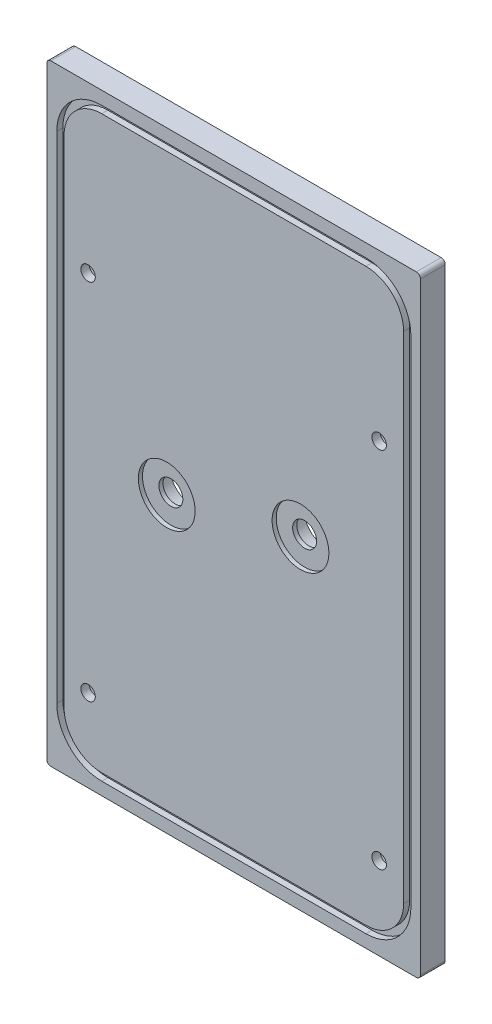
SolidWorks part; units mm, degrees
material "Melamine resin"
ref_plane "Plano frontal" through (0, 0, 0) normal (0, 0, 1) x (1, 0, 0)
ref_plane "Plano superior" through (0, 0, 0) normal (0, 1, 0) x (1, 0, 0)
ref_plane "Plano direito" through (0, 0, 0) normal (1, 0, 0) x (0, 0, -1)
sketch "Esboço1" plane through (0, 0, 0) normal (0, 0, 1) x (1, 0, 0)
  line L1 (-90.5, -148) -> (90.5, -148)
  line L2 (-90.5, -148) -> (-90.5, 148)
  line L3 (-90.5, 148) -> (90.5, 148)
  line L4 (90.5, -148) -> (90.5, 148)
  line L5 (-90.5, -148) -> (90.5, 148) construction
  line L6 (-90.5, 148) -> (90.5, -148) construction
  point P0 (0, 0)
  dimension "D1" = 181
  dimension "D2" = 296
extrude "Ressalto-extrusão1" add sketch "Esboço1" along normal blind 12
fillet "Filete1" radius 2 1 edges at (-90.5, 148, 6)
fillet "Filete2" radius 2 3 edges at (-90.5, -148, 6) (90.5, -148, 6) (90.5, 148, 6)
sketch "Esboço2" plane through (0, 0, 12) normal (0, 0, 1) x (1, 0, 0)
  line L5 (-63.9, -140.1) -> (64.1, -140.1)
  line L6 (-83.9, -120.1) -> (-83.9, 119.9)
  line L7 (-63.9, 139.9) -> (64.1, 139.9)
  line L8 (84.1, -120.1) -> (84.1, 119.9)
  line L9 (-83.9, -140.1) -> (84.1, 139.9) construction
  line L10 (-83.9, 139.9) -> (84.1, -140.1) construction
  arc A0 (84.1, -120.1) -> (64.1, -140.1) centre (64.1, -120.1) cw
  arc A1 (-63.9, -140.1) -> (-83.9, -120.1) centre (-63.9, -120.1) cw
  arc A2 (-63.9, 139.9) -> (-83.9, 119.9) centre (-63.9, 119.9) ccw
  arc A3 (84.1, 119.9) -> (64.1, 139.9) centre (64.1, 119.9) ccw
  point P6 (0.1, -0.1)
  dimension "D3" = 20
  dimension "D1" = 168
  dimension "D2" = 280
sketch "Esboço4" plane through (0, 0, 0) normal (0, 1, 0) x (1, 0, 0)
  line L0 (-83.9, -12) -> (-63.9, -12) construction
  line L2 (-85.665, -12.565) -> (-82.135, -12.565)
  line L3 (-85.665, -12.565) -> (-85.665, -9.035)
  line L4 (-85.665, -9.035) -> (-82.135, -9.035)
  line L5 (-82.135, -12.565) -> (-82.135, -9.035)
  line L6 (-85.665, -12.565) -> (-82.135, -9.035) construction
  line L7 (-85.665, -9.035) -> (-82.135, -12.565) construction
  circle A0 centre (-83.9, -10.8) radius 1.765 construction
  dimension "D1" = 3.53
  dimension "D2" = 1.2
sweep "Varredura de corte1" cut profiles "Esboço4" path "Esboço2"
sketch "Esboço6" plane through (0, 0, 0) normal (0, 0, 1) x (1, 0, 0)
  line L0 (88.5, 148) -> (-88.5, 148) construction
  line L1 (-70.5, -108) -> (70.5, -108) construction
  line L2 (-70.5, -108) -> (-70.5, 68) construction
  line L3 (-70.5, 68) -> (70.5, 68) construction
  line L4 (70.5, -108) -> (70.5, 68) construction
  line L5 (-70.5, -108) -> (70.5, 68) construction
  line L6 (-70.5, 68) -> (70.5, -108) construction
  line L8 (-90.5, 146) -> (-90.5, -146) construction
  line L9 (-88.5, -148) -> (88.5, -148) construction
  point P0 (0, 0)
  dimension "D1" = 80
  dimension "D2" = 20
  dimension "D3" = 40
hole_wizard "Rebaixo para parafuso com cabeça panela de M61" positions "Esboço8" profile "Esboço7" counterbore size "M6" standard "ISO" end condition through all
sketch "Esboço8" plane through (0, 0, 0) normal (0, 0, -1) x (-1, 0, 0)
  point P0 (-70.5, 68)
  point P1 (70.5, 68)
  point P4 (70.5, -108)
  point P7 (-70.5, -108)
sketch "Esboço7" plane through (70.5, 68, 0) normal (1, 0, 0) x (0, 1, 0)
  line L0 (0, 0) -> (0, 12)
  line L1 (0, 12) -> (3.5, 12)
  line L3 (3.5, 12) -> (3.5, 8)
  line L4 (3.5, 8) -> (6.5, 8)
  line L5 (6.5, 8) -> (6.5, 0)
  line L7 (6.5, 0) -> (0, 0)
  line L11 (0, -6.35) -> (0, 107.95) construction
  dimension "Thru Hole Dia." = 7
  dimension "Thru Hole Depth" = 12
  dimension "C'Bore Dia." = 13
  dimension "C'Bore Depth" = 8
sketch "Esboço9" plane through (0, 0, 0) normal (0, 0, -1) x (-1, 0, 0)
  line L0 (-90.5, -146) -> (-90.5, 146) construction
  line L1 (90.5, 146) -> (90.5, -146) construction
  line L2 (-88.5, 148) -> (88.5, 148) construction
  circle A0 centre (32.4, -6) radius 5.8
  circle A1 centre (-32.4, 8.8) radius 5.8
  dimension "D1" = 11.6
  dimension "D2" = 11.6
  dimension "D3" = 58.1
  dimension "D4" = 58.1
  dimension "D5" = 139.2
  dimension "D6" = 154
extrude "Corte-extrusão1" cut sketch "Esboço9" against normal up to next
sketch "Esboço10" plane through (0, 0, 0) normal (0, 0, -1) x (-1, 0, 0)
  line L0 (-32.4, 8.8) -> (-32.4, 31.045) construction
  line L1 (32.4, -6) -> (32.4, 18.3317) construction
  circle A0 centre (32.4, -6) radius 10.275
  circle A1 centre (-32.4, 8.8) radius 10.275
  dimension "D1" = 20.55
  dimension "D2" = 20.55
extrude "Corte-extrusão2" cut sketch "Esboço10" against normal blind 8
sketch "Esboço11" plane through (0, 0, 12) normal (0, 0, 1) x (1, 0, 0)
  circle A0 centre (32.4, 8.8) radius 13.75
  circle A1 centre (-32.4, -6) radius 13.75
  dimension "D1" = 27.5
  dimension "D2" = 27.5
extrude "Corte-extrusão3" cut sketch "Esboço11" against normal blind 2
sketch "Esboço12" plane through (0, 0, 0) normal (0, 0, -1) x (-1, 0, 0)
  line L0 (-32.4, 19.075) -> (-32.4, 25.075) construction
  line L1 (-33.4, 19.075) -> (-33.4, 25.075)
  line L2 (-31.4, 19.075) -> (-31.4, 25.075)
  circle A0 centre (-32.4, 8.8) radius 10.275 construction
  circle A1 centre (-32.4, 8.8) radius 10.275 construction
  arc A2 (-33.4, 19.075) -> (-31.4, 19.075) centre (-32.4, 19.075) ccw
  arc A3 (-31.4, 25.075) -> (-33.4, 25.075) centre (-32.4, 25.075) ccw
  point P7 (-32.4, 22.075)
  dimension "D1" = 2
  dimension "D2" = 6
extrude "Corte-extrusão4" cut sketch "Esboço12" against normal blind 1.4
sketch "Esboço13" plane through (0, 0, 0) normal (0, 0, -1) x (-1, 0, 0)
  line L0 (32.4, 4.275) -> (32.4, 9.275) construction
  line L1 (31.4, 4.275) -> (31.4, 9.275)
  line L2 (33.4, 4.275) -> (33.4, 9.275)
  circle A0 centre (32.4, -6) radius 10.275 construction
  circle A1 centre (32.4, -6) radius 10.275 construction
  arc A2 (31.4, 4.275) -> (33.4, 4.275) centre (32.4, 4.275) ccw
  arc A3 (33.4, 9.275) -> (31.4, 9.275) centre (32.4, 9.275) ccw
  point P7 (32.4, 6.775)
  dimension "D1" = 2
  dimension "D2" = 5
extrude "Corte-extrusão5" cut sketch "Esboço13" against normal blind 1.4
